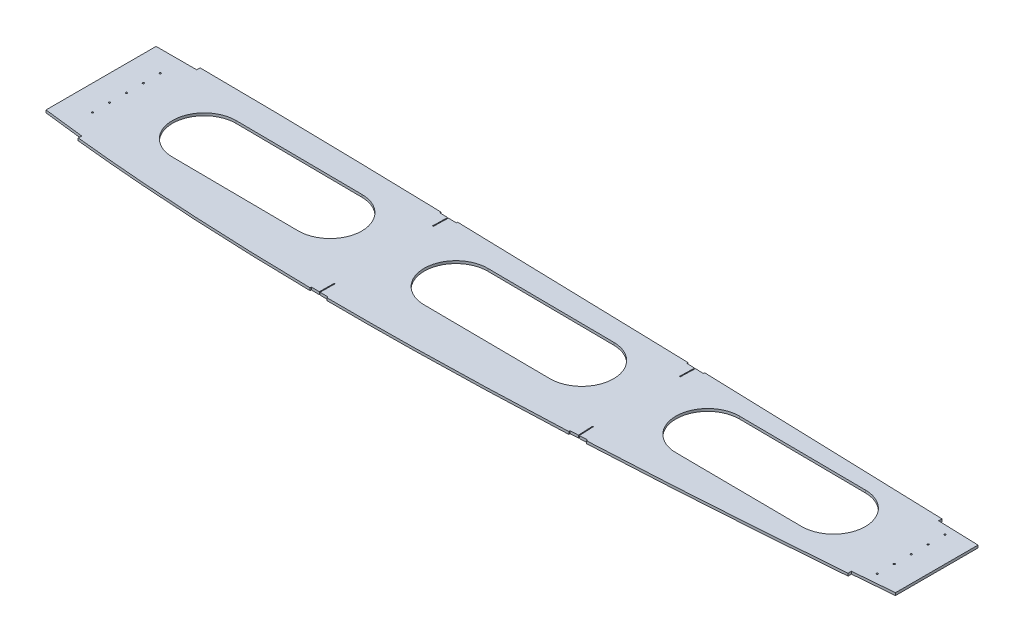
SolidWorks part; units mm, degrees
ref_plane "Front Plane" through (0, 0, 0) normal (0, 0, 1) x (1, 0, 0)
ref_plane "Top Plane" through (0, 0, 0) normal (0, 1, 0) x (1, 0, 0)
ref_plane "Right Plane" through (0, 0, 0) normal (1, 0, 0) x (0, 0, -1)
curve "Curve1"
  spline degree 3 poles (4000, 0, 3.36) (3933.7952, 0, 13.7836) (3801.3288, 0, 34.6398) (3535.8598, 0, 72.9041) (3203.3086, 0, 115.6254) (2803.4291, 0, 159.0217) (2402.8529, 0, 194.3246) (2001.6907, 0, 220.4636) (1599.3709, 0, 237.3526) (1263.2444, 0, 238.5562) (993.9739, 0, 228.1238) (792.1965, 0, 214.0116) (590.7612, 0, 192.5716) (423.6273, 0, 166.9066) (290.5285, 0, 139.3108) (190.9422, 0, 115.3098) (107.85, 0, 83.2401) (41.1412, 0, 57.7125) (-26.5303, 0, -2.7796) (51.7418, 0, -47.9035) (120.8588, 0, -63.3442) (208.0782, 0, -76.9163) (308.6135, 0, -84.9268) (442.4147, 0, -91.4528) (608.5618, 0, -94.255) (807.5001, 0, -93.1942) (1005.8652, 0, -89.7827) (1269.9834, 0, -83.4685) (1600.8258, 0, -74.8684) (1998.599, 0, -63.7434) (2397.4918, 0, -50.4963) (2796.9631, 0, -37.5709) (3197.1451, 0, -25.2391) (3531.1287, 0, -15.9133) (3798.838, 0, -8.6469) (3932.8931, 0, -5.1237) (4000, 0, -3.36) knots 0 0 0 0 0.02488 0.049781 0.099567 0.14934 0.199092 0.248839 0.298568 0.348561 0.373567 0.398591 0.423638 0.448742 0.461353 0.474029 0.486955 0.493558 0.502381 0.511191 0.517824 0.530564 0.54309 0.555505 0.580209 0.604805 0.629344 0.653862 0.702881 0.752206 0.801586 0.851045 0.900581 0.950217 0.975079 1 1 1 1
sketch "Sketch1" plane through (0, 0, 0) normal (0, 1, 0) x (1, 0, 0)
  line L3 (2600, 39.9641) -> (2600, -170.5868)
  line L5 (600, 93.4646) -> (600, -192.1843)
  line L6 (699.3254, -197.7806) -> (700.1696, -189.8252)
  line L10 (700.1696, -189.8252) -> (600, -178.1843)
  line L12 (699.9999, 89.6131) -> (699.9732, 81.6131)
  line L16 (699.9732, 81.6131) -> (600, 81.4646)
  line L18 (604, 81.4705) -> (604, -178.6491)
  line L23 (2500.0525, 43.2029) -> (2499.7923, 35.2071)
  line L26 (2499.7923, 35.2071) -> (2600, 31.9641)
  line L32 (2499.7035, -171.0738) -> (2600, -162.5868)
  line L34 (2596, -162.9253) -> (2596, 32.0935)
  line L36 (1300, -230.8258) -> (1300.0318, -227.8519)
  line L40 (1279.9937, -230.5861) -> (1280.0336, -227.5864)
  line L41 (1320.0064, -231.0142) -> (1320.03, -228.1174)
  line L42 (1280.0336, -227.5864) -> (1320.03, -228.1174)
  line L44 (1299.0319, -227.8387) -> (1299.4965, -192.8417)
  line L45 (1301.0317, -227.8652) -> (1301.4964, -192.8683)
  line L46 (1299.4965, -192.8417) -> (1301.4964, -192.8683)
  line L47 (1900, -218.0453) -> (1899.8579, -215.0352)
  line L50 (1880.0175, -218.9751) -> (1879.8801, -215.9782)
  line L51 (1919.9811, -217.0886) -> (1919.8356, -214.0922)
  line L52 (1879.8801, -215.9782) -> (1919.8356, -214.0922)
  line L54 (1898.859, -215.0824) -> (1897.2087, -180.1213)
  line L55 (1900.8568, -214.9881) -> (1899.2065, -180.027)
  line L56 (1897.2087, -180.1213) -> (1899.2065, -180.027)
  line L57 (1900, 62.3483) -> (1899.9119, 59.3496)
  line L60 (1880.0086, 62.936) -> (1919.9914, 61.7607)
  line L61 (1880.0086, 62.936) -> (1879.9205, 59.9373)
  line L62 (1919.9914, 61.7607) -> (1919.9032, 58.762)
  line L63 (1879.9205, 59.9373) -> (1919.9032, 58.762)
  line L65 (1898.9123, 59.379) -> (1897.884, 24.3941)
  line L66 (1900.9114, 59.3203) -> (1899.8831, 24.3354)
  line L67 (1897.884, 24.3941) -> (1899.8831, 24.3354)
  line L68 (1300, 78.6065) -> (1299.9242, 75.6062)
  line L71 (1280.0059, 79.1101) -> (1279.9306, 76.1111)
  line L72 (1319.994, 78.1003) -> (1319.9179, 75.1013)
  line L73 (1279.9306, 76.1111) -> (1319.9179, 75.1013)
  line L75 (1298.9245, 75.6314) -> (1298.041, 40.6426)
  line L76 (1300.9239, 75.5809) -> (1300.0403, 40.5921)
  line L77 (1298.041, 40.6426) -> (1300.0403, 40.5921)
  line L78 (604, -48.5893) -> (2596, -65.4159)
  line L79 (850.0053, -50.6673) -> (1149.9946, -53.2014) construction
  line L80 (2050.0053, -60.8038) -> (2349.9946, -63.3379) construction
  line L81 (850.6389, 24.33) -> (1150.6282, 21.796)
  line L82 (849.3718, -125.6647) -> (1149.3611, -128.1987)
  line L83 (1450.0053, -55.7356) -> (1749.9946, -58.2696) construction
  line L84 (1450.6389, 19.2617) -> (1750.6282, 16.7277)
  line L85 (1449.3718, -130.7329) -> (1749.3611, -133.2669)
  line L87 (2050.6389, 14.1935) -> (2350.6282, 11.6595)
  line L88 (2049.3718, -135.8012) -> (2349.3611, -138.3352)
  line L90 (2500.3585, -179.0469) -> (2499.7035, -171.0738)
  arc A0 (850.6389, 24.33) -> (849.3718, -125.6647) centre (850.0053, -50.6673) ccw
  arc A1 (1149.3611, -128.1987) -> (1150.6282, 21.796) centre (1149.9946, -53.2014) ccw
  arc A2 (1450.6389, 19.2617) -> (1449.3718, -130.7329) centre (1450.0053, -55.7356) ccw
  arc A3 (1749.3611, -133.2669) -> (1750.6282, 16.7277) centre (1749.9946, -58.2696) ccw
  arc A4 (2050.6389, 14.1935) -> (2049.3718, -135.8012) centre (2050.0053, -60.8038) ccw
  arc A5 (2349.3611, -138.3352) -> (2350.6282, 11.6595) centre (2349.9946, -63.3379) ccw
  spline S3 degree 3 poles (600, 89.4646) (602.96, 89.4846) (672.1595, 89.9159) (807.5001, 89.1942) (1005.8652, 85.7827) (1269.9834, 79.4685) (1600.8258, 70.8684) (1998.599, 59.7434) (2331.9077, 48.6743) (2532.4261, 42.1441) (2600, 39.9641) knots 0.57911 0.57911 0.57911 0.57911 0.580209 0.604805 0.629344 0.653862 0.702881 0.752206 0.801586 0.826685 0.826685 0.826685 0.826685
  spline S4 degree 3 poles (2600, -170.5868) (2534.2697, -176.3468) (2334.9532, -192.7488) (2001.6907, -214.4636) (1599.3709, -231.3526) (1263.2444, -232.5562) (993.9739, -222.1238) (795.1742, -208.2199) (663.9659, -194.3608) (600, -186.1843) knots 0.174598 0.174598 0.174598 0.174598 0.199092 0.248839 0.298568 0.348561 0.373567 0.398591 0.42253 0.42253 0.42253 0.42253
  point P80 (1600, -57.0026)
  point P84 (2200, -62.0708)
  point P86 (1000, -51.9343)
  point P91 (1000, -51.9343)
  point P97 (1600, -57.0026)
  point P105 (2200, -62.0708)
  point P121 (1600, -228.76)
  dimension "D5" = 8
  dimension "D6" = 100
  dimension "D7" = 4
  dimension "D8" = 8
  dimension "D9" = 100
  dimension "D10" = 8
  dimension "D11" = 8
  dimension "D12" = 1000
  dimension "D13" = 19
  dimension "D14" = 3
  dimension "D15" = 19
  dimension "D16" = 8
  dimension "D17" = 1
  dimension "D18" = 1
  dimension "D19" = 35
  dimension "D21" = 300
  dimension "D22" = 3
  dimension "D23" = 20
  dimension "D24" = 20
  dimension "D25" = 1
  dimension "D26" = 1
  dimension "D27" = 35
  dimension "D28" = 3
  dimension "D29" = 1
  dimension "D30" = 1
  dimension "D31" = 19
  dimension "D32" = 300
  dimension "D33" = 35
  dimension "D34" = 3
  dimension "D35" = 1
  dimension "D36" = 1
  dimension "D37" = 19
  dimension "D38" = 19
  dimension "D39" = 35
  dimension "D40" = 600
  dimension "D41" = 600
  dimension "D42" = 150
  dimension "D43" = 75
  dimension "D44" = 300
  dimension "D45" = 300
  dimension "19m" = 19
  dimension "D46" = 100
  dimension "D47" = 8
  dimension "D48" = 4
  dimension "D49" = 8
  dimension "D50" = 100
  dimension "D51" = 8
extrude "Boss-Extrude1" add sketch "Sketch1" along normal blind 6
hole_wizard "Ø4.0mm Dowel Hole1" positions "Sketch2" profile "Sketch3" hole size "Ø4.0" standard "ISO" end condition through all
sketch "Sketch2" plane through (965.9468, -0.0963, -62.9537) normal (0.0001, -1, 0) x (1, 0.0001, 0)
  point P0 (1569.8739, 128.5294)
  point P1 (1569.8739, 168.5294)
  point P2 (1569.8739, 208.5294)
  point P3 (1569.8739, 88.5294)
  point P4 (1569.8739, 48.5294)
sketch "Sketch3" plane through (2535.8207, 0, 65.5757) normal (1, 0, 0) x (0, 0, -1)
  line L0 (0, 0) -> (0, 6)
  line L1 (0, 6) -> (2, 6)
  line L2 (2, 6) -> (2, 0)
  line L3 (2, 0) -> (0, 0)
  line L4 (0, -6.35) -> (0, 107.95) construction
  dimension "Thru Hole Dia." = 4
  dimension "Thru Hole Depth" = 6
hole_wizard "Ø4.0mm Dowel Hole2" positions "Sketch4" profile "Sketch5" hole size "Ø4.0" standard "JIS" end condition through all
sketch "Sketch4" plane through (965.9468, -0.0185, -62.9537) normal (-0.0001, -1, 0) x (1, -0.0001, 0)
  point P0 (-301.7717, 111.6597)
  point P1 (-301.7717, 191.6597)
  point P2 (-301.7717, 151.6597)
  point P3 (-301.7717, 31.6597)
  point P4 (-301.7717, 71.6597)
sketch "Sketch5" plane through (664.1751, 0, 48.706) normal (1, 0, 0) x (0, 0, -1)
  line L0 (0, 0) -> (0, 6)
  line L1 (0, 6) -> (2, 6)
  line L2 (2, 6) -> (2, 0)
  line L3 (2, 0) -> (0, 0)
  line L4 (0, -6.35) -> (0, 107.95) construction
  dimension "Thru Hole Dia." = 4
  dimension "Thru Hole Depth" = 6
